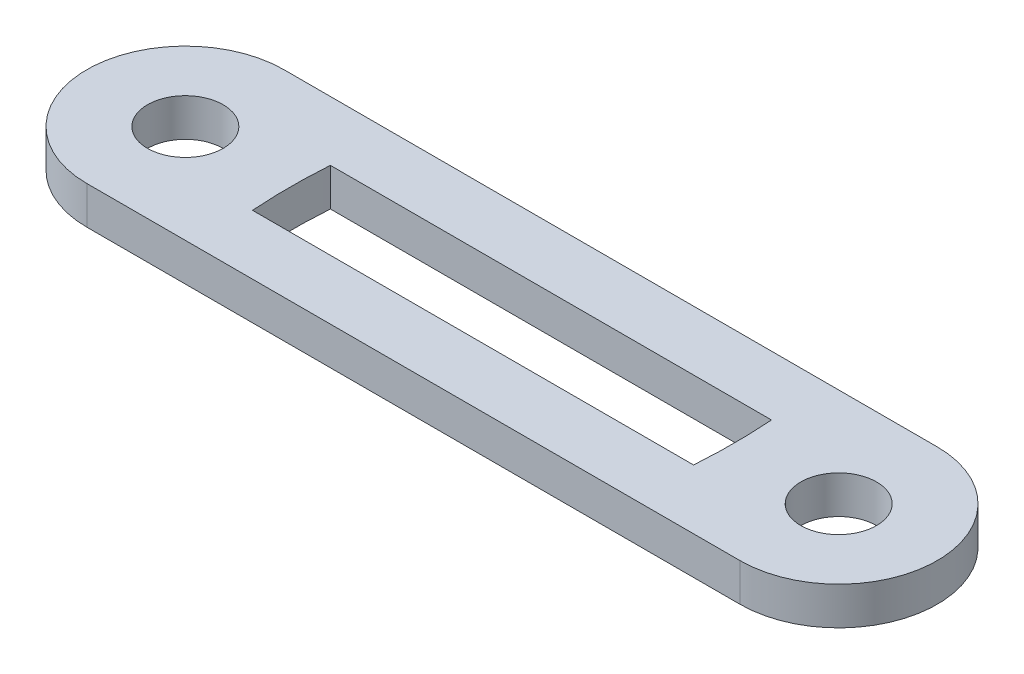
SolidWorks part; units mm, degrees
material "6061-T6 (SS)"
ref_plane "Front Plane" through (0, 0, 0) normal (0, 0, 1) x (1, 0, 0)
ref_plane "Top Plane" through (0, 0, 0) normal (0, 1, 0) x (1, 0, 0)
ref_plane "Right Plane" through (0, 0, 0) normal (1, 0, 0) x (0, 0, -1)
sketch "Sketch1" plane through (0, 0, 0) normal (0, 1, 0) x (1, 0, 0)
  line L0 (-13.7, 0) -> (13.7, 0) construction
  line L1 (13.7, 4.1337) -> (-13.7, 4.1337)
  line L3 (-13.7, -4.1337) -> (13.7, -4.1337)
  line L4 (9.2493, -1.6337) -> (-9.2493, -1.6337)
  line L5 (-9.2493, 1.6337) -> (9.2493, 1.6337)
  line L6 (13.7, 1.6337) -> (-13.7, 1.6337) construction
  line L7 (-13.7, -1.6337) -> (13.7, -1.6337) construction
  circle A0 centre (13.7, 0) radius 1.5875
  circle A1 centre (-13.7, 0) radius 1.5875
  arc A2 (-13.7, 4.1337) -> (-13.7, -4.1337) centre (-13.7, 0) ccw
  arc A3 (13.7, -4.1337) -> (13.7, 4.1337) centre (13.7, 0) ccw
  circle A4 centre (-9.4564, 0) radius 0.5953 construction
  circle A5 centre (-4.9564, 0) radius 0.5953 construction
  arc A6 (9.2493, 1.6337) -> (9.2493, -1.6337) centre (-13.7, 0) cw
  arc A7 (13.7, -1.6337) -> (13.7, 1.6337) centre (13.7, 0) ccw
  arc A8 (-13.7, 1.6337) -> (-13.7, -1.6337) centre (-13.7, 0) ccw construction
  arc A9 (-9.2493, 1.6337) -> (-9.2493, -1.6337) centre (13.7, 0) ccw
  point P3 (0, 0)
  dimension "D2" = 3.175
  dimension "D3" = 1.1906
  dimension "D4" = 4.5
  dimension "D1" = 27.4
  dimension "D5" = 2.5
  dimension "D6" = 2.5
extrude "Boss-Extrude2" add sketch "Sketch1" along normal mid plane 1.5875
